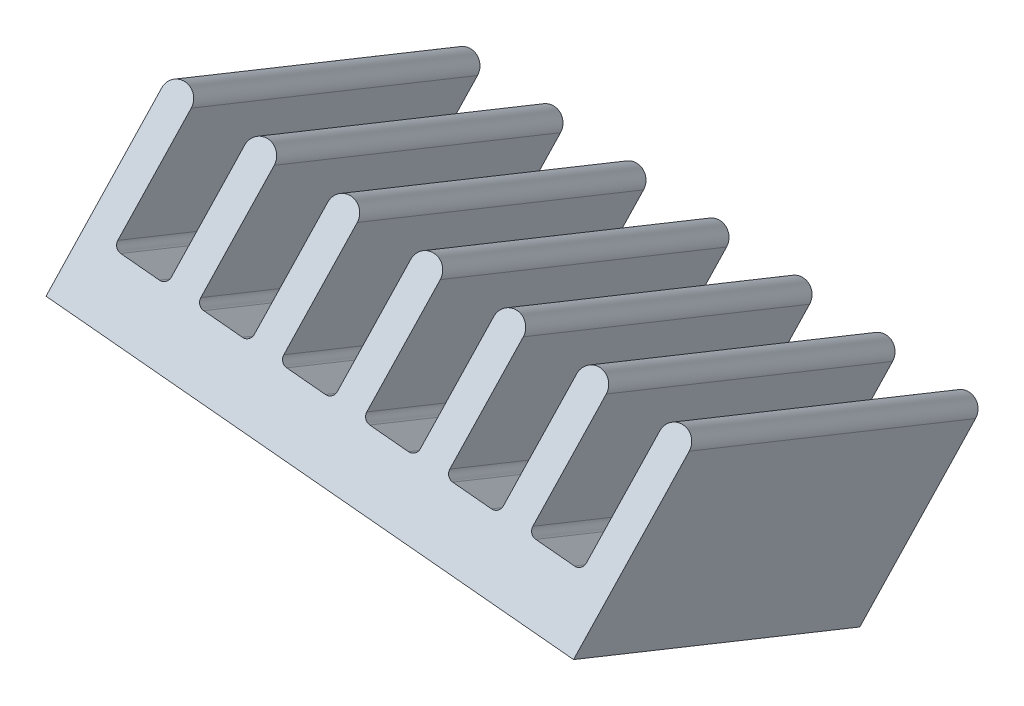
SolidWorks part; units mm, degrees
ref_plane "Front Plane" through (0, 0, 0) normal (0, 0, 1) x (1, 0, 0)
ref_plane "Top Plane" through (0, 0, 0) normal (0, 1, 0) x (1, 0, 0)
ref_plane "Right Plane" through (0, 0, 0) normal (1, 0, 0) x (0, 0, -1)
sketch "Sketch2" plane through (-2.5869, -15.6993, 9.7875) normal (0.1385, 0.8404, -0.5239) x (0.9597, -0.2445, -0.1385)
  line L13 (13.0487, -7.5761) -> (27.3487, -7.5761)
  line L14 (13.0487, -7.5761) -> (13.0487, 6.7239)
  line L15 (13.0487, 6.7239) -> (27.3487, 6.7239)
  line L24 (27.3487, -7.5761) -> (27.3487, 6.7239)
  line L25 (13.0487, -7.5761) -> (27.3487, 6.7239) construction
  line L26 (13.0487, 6.7239) -> (27.3487, -7.5761) construction
  point P0 (20.1987, -0.4261)
  point P2 (20.1987, -0.4261)
  dimension "D1" = 14.3
  dimension "D2" = 14.3
extrude "Boss-Extrude1" add sketch "Sketch2" along normal blind 5.6
sketch "Sketch3" plane through (-1.6438, -3.2521, -5.6509) normal (-0.2445, -0.4837, -0.8404) x (-0.9697, 0.1219, 0.2119)
  line L8 (-17.6706, -16.1697) -> (-17.1993, -19.4359)
  line L9 (-16.2354, -15.9626) -> (-15.7641, -19.2288)
  line L10 (-16.9728, -19.6053) -> (-15.9335, -19.4553)
  line L11 (-18.1236, -15.8309) -> (-17.0096, -23.551) construction
  line L12 (-25.2003, -16.852) -> (-11.0469, -14.8098) construction
  line L17 (-15.8966, -15.5096) -> (-15.2633, -19.8987) construction
  line L18 (-18.1236, -15.8309) -> (-15.8966, -15.5096)
  line L30 (-9.4499, -14.8447) -> (-9.4033, -14.8457)
  arc A4 (-17.6706, -16.1697) -> (-18.1236, -15.8309) centre (-18.0665, -16.2268) ccw
  arc A12 (-17.1993, -19.4359) -> (-16.9728, -19.6053) centre (-17.0013, -19.4073) ccw
  arc A13 (-15.7641, -19.2288) -> (-15.9335, -19.4553) centre (-15.9621, -19.2574) cw
  arc A14 (-16.2354, -15.9626) -> (-15.8966, -15.5096) centre (-15.8395, -15.9055) cw
  dimension "D1" = 0.2
  dimension "D2" = 0.2
  dimension "D3" = 0.4
  dimension "D4" = 0.4
  dimension "D5" = 3.3
  dimension "D6" = 3.3
  dimension "D7" = 1.05
extrude "Cut-Extrude2" cut sketch "Sketch3" against normal blind 17.5
pattern_linear "LPattern1" count 5 spacing 2.25 along (0.9597, -0.2445, -0.1385) count 4 spacing 2.25 along (-0.9597, 0.2445, 0.1385) of "Cut-Extrude2"
